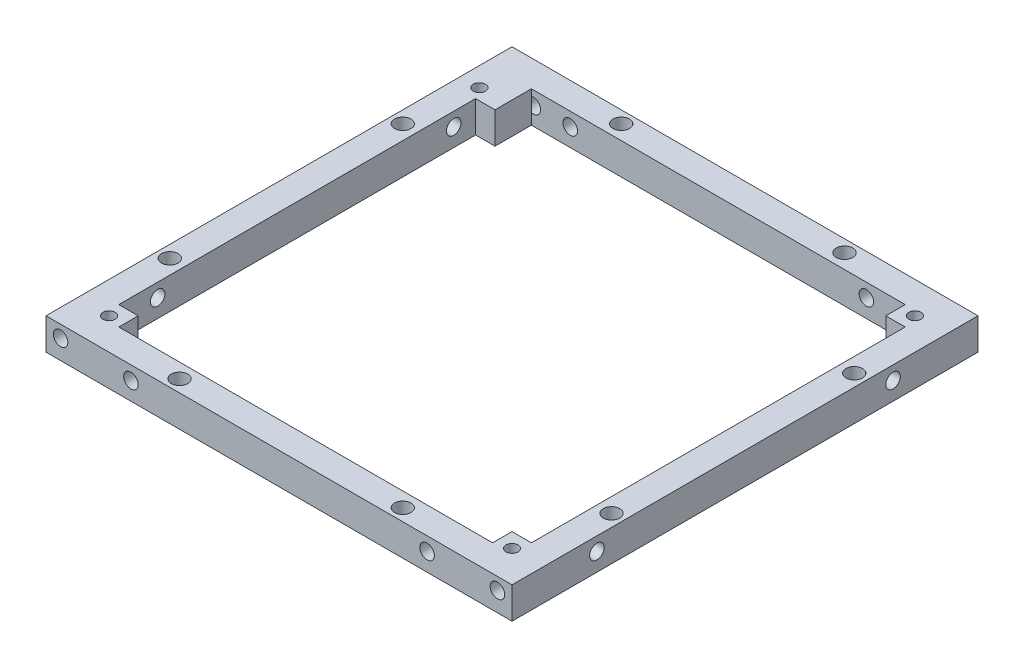
SolidWorks part; units mm, degrees
material "Aluminum"
ref_plane "Front Plane" through (0, 0, 0) normal (0, 0, 1) x (1, 0, 0)
ref_plane "Top Plane" through (0, 0, 0) normal (0, 1, 0) x (1, 0, 0)
ref_plane "Right Plane" through (0, 0, 0) normal (1, 0, 0) x (0, 0, -1)
sketch "Sketch1" plane through (0, 0, 0) normal (0, 1, 0) x (1, 0, 0)
  line L1 (48, -48) -> (-48, -48)
  line L2 (48, -48) -> (48, 48)
  line L3 (48, 48) -> (-48, 48)
  line L4 (-48, -48) -> (-48, 48)
  line L5 (48, -48) -> (-48, 48) construction
  line L6 (48, 48) -> (-48, -48) construction
  line L7 (40, -40) -> (-40, -40)
  line L8 (40, -40) -> (40, 40)
  line L9 (40, 40) -> (-40, 40)
  line L10 (-40, -40) -> (-40, 40)
  line L11 (40, -40) -> (-40, 40) construction
  line L12 (40, 40) -> (-40, -40) construction
  point P0 (0, 0)
  point P6 (0, 0)
  dimension "D1" = 96
  dimension "D2" = 96
  dimension "D3" = 8
extrude "Boss-Extrude1" add sketch "Sketch1" along normal blind 8
hole_wizard "Ø3.0 (3) Diameter Hole6" positions "Sketch8" profile "Sketch7" hole size "Ø3.0" standard "ANSI Metric"
sketch "Sketch8" plane through (0, 0, 48) normal (0, 0, 1) x (1, 0, 0)
  line L0 (48, 8) -> (48, 0) construction
  line L1 (-48, 8) -> (-48, 0) construction
  line L2 (-48, 0) -> (48, 0) construction
  point P0 (45, 4)
  point P2 (-45, 4)
  dimension "D1" = 3
  dimension "D2" = 3
  dimension "D3" = 4
  dimension "D4" = 4
sketch "Sketch7" plane through (45, 4, 48) normal (1, 0, 0) x (0, -1, 0)
  line L0 (0, 0) -> (0, 7.5)
  line L1 (0, 7.5) -> (1.5, 7.5)
  line L2 (1.5, 7.5) -> (1.5, 0)
  line L5 (1.5, 0) -> (0, 0)
  line L10 (0, 7.5) -> (-1.5, 7.5) construction
  line L11 (0, -6.35) -> (0, 107.95) construction
  dimension "Hole Dia." = 3
  dimension "Hole Depth" = 7.5
  dimension "Drill Angle" = 180
hole_wizard "Ø3.0 (3) Diameter Hole3" positions "Sketch10" profile "Sketch9" hole size "Ø3.0" standard "ANSI Metric"
sketch "Sketch10" plane through (0, 0, -48) normal (0, 0, -1) x (-1, 0, 0)
  line L0 (-48, 8) -> (-48, 0) construction
  line L1 (48, 8) -> (48, 0) construction
  line L2 (-48, 0) -> (48, 0) construction
  point P0 (-45, 4)
  point P2 (45, 4)
  dimension "D1" = 3
  dimension "D2" = 3
  dimension "D3" = 4
  dimension "D4" = 4
sketch "Sketch9" plane through (45, 4, -48) normal (1, 0, 0) x (0, 1, 0)
  line L0 (0, 0) -> (0, 7.5)
  line L1 (0, 7.5) -> (1.5, 7.5)
  line L2 (1.5, 7.5) -> (1.5, 0)
  line L5 (1.5, 0) -> (0, 0)
  line L10 (0, 7.5) -> (-1.5, 7.5) construction
  line L11 (0, -6.35) -> (0, 107.95) construction
  dimension "Hole Dia." = 3
  dimension "Hole Depth" = 7.5
  dimension "Drill Angle" = 180
sketch "Sketch27" plane through (0, 8, 0) normal (0, 1, 0) x (1, 0, 0)
  line L0 (-40, 40) -> (-40, -40) construction
  line L1 (41, -41) -> (-41, -41)
  line L2 (41, -41) -> (41, 41)
  line L3 (41, 41) -> (-41, 41)
  line L4 (-41, -41) -> (-41, 41)
  line L5 (41, -41) -> (-41, 41) construction
  line L6 (41, 41) -> (-41, -41) construction
  line L7 (40, 40) -> (-40, 40) construction
  point P0 (0, 0)
  dimension "D1" = 1
  dimension "D2" = 1
extrude "Cut-Extrude2" cut sketch "Sketch27" against normal blind 10
hole_wizard "Ø3.4 (3.4) Diameter Hole1" positions "Sketch37" profile "Sketch36" hole size "Ø3.4" standard "ANSI Metric" end condition through all
sketch "Sketch37" plane through (0, 0, 0) normal (0, -1, 0) x (-1, 0, 0)
  point P0 (-23, 45.5)
  point P2 (23, 45.5)
  point P4 (45.5, 23)
  point P6 (45.5, -25)
  point P8 (23, -45.5)
  point P10 (-23, -45.5)
  point P12 (-45.5, -25)
  point P14 (-45.5, 25)
sketch "Sketch36" plane through (23, 0, -45.5) normal (1, 0, 0) x (0, 0, -1)
  line L0 (0, 0) -> (0, 8)
  line L1 (0, 8) -> (1.7, 8)
  line L2 (1.7, 8) -> (1.7, 0)
  line L5 (1.7, 0) -> (0, 0)
  line L11 (0, -6.35) -> (0, 107.95) construction
  dimension "Thru Hole Dia." = 3.4
  dimension "Thru Hole Depth" = 8
sketch "Sketch38" plane through (0, 8, 0) normal (0, 1, 0) x (1, 0, 0)
  line L0 (48, 48) -> (-48, 48) construction
  line L1 (42.5, -42.5) -> (-42.5, -42.5)
  line L2 (42.5, -42.5) -> (42.5, 42.5)
  line L3 (42.5, 42.5) -> (-42.5, 42.5)
  line L4 (-42.5, -42.5) -> (-42.5, 42.5)
  line L5 (42.5, -42.5) -> (-42.5, 42.5) construction
  line L6 (42.5, 42.5) -> (-42.5, -42.5) construction
  line L7 (-48, 48) -> (-48, -48) construction
  point P0 (0, 0)
  dimension "D1" = 5.5
  dimension "D2" = 5.5
extrude "Cut-Extrude4" cut sketch "Sketch38" against normal blind 10
sketch "Sketch44" plane through (0, 0, 0) normal (0, -1, 0) x (1, 0, 0)
  line L0 (42.5, -42.5) -> (-42.5, -42.5) construction
  line L1 (42.5, -42.5) -> (38.5, -42.5)
  line L2 (42.5, -42.5) -> (42.5, -38.5)
  line L3 (42.5, -38.5) -> (38.5, -38.5)
  line L4 (38.5, -42.5) -> (38.5, -38.5)
  line L5 (42.5, 42.5) -> (42.5, -42.5) construction
  line L6 (0, 0) -> (0, -67.1068) construction
  line L7 (0, 0) -> (66.4168, 0) construction
  line L8 (-38.5, -42.5) -> (-38.5, -38.5)
  line L9 (-42.5, -38.5) -> (-38.5, -38.5)
  line L10 (-42.5, -42.5) -> (-42.5, -38.5)
  line L11 (-42.5, -42.5) -> (-38.5, -42.5)
  line L12 (-42.5, 42.5) -> (-38.5, 42.5)
  line L13 (-42.5, 42.5) -> (-42.5, 38.5)
  line L14 (-42.5, 38.5) -> (-38.5, 38.5)
  line L15 (-38.5, 42.5) -> (-38.5, 38.5)
  line L16 (38.5, 42.5) -> (38.5, 38.5)
  line L17 (42.5, 38.5) -> (38.5, 38.5)
  line L18 (42.5, 42.5) -> (42.5, 38.5)
  line L19 (42.5, 42.5) -> (38.5, 42.5)
  dimension "D1" = 4
  dimension "D2" = 4
extrude "Boss-Extrude2" add sketch "Sketch44" against normal blind 8
sketch "Sketch45" plane through (0, 8, 0) normal (0, 1, 0) x (1, 0, 0)
  line L1 (-42.5, 38.5) -> (-38.5, 38.5)
  line L2 (-42.5, 38.5) -> (-42.5, 35)
  line L3 (-42.5, 35) -> (-38.5, 35)
  line L4 (-38.5, 38.5) -> (-38.5, 35)
  dimension "D1" = 4
  dimension "D2" = 3.5
extrude "Boss-Extrude3" add sketch "Sketch45" against normal blind 8
hole_wizard "Tap Drill for M3x0.5 Tap1" positions "Sketch48" profile "Sketch46" hole size "M3x0.5" standard "ANSI Metric" end condition through all
sketch "Sketch48" plane through (0, 8, 0) normal (0, 1, 0) x (1, 0, 0)
  point P0 (41.5, 41.5)
  point P2 (41.5, -41.5)
  point P4 (-41.5, -41.5)
  point P6 (-44.05, 37.33)
sketch "Sketch46" plane through (41.5, 8, -41.5) normal (1, 0, 0) x (0, 0, 1)
  line L0 (0, 0) -> (0, 8)
  line L1 (0, 8) -> (1.25, 8)
  line L2 (1.25, 8) -> (1.25, 0)
  line L5 (1.25, 0) -> (0, 0)
  line L11 (0, -6.35) -> (0, 107.95) construction
  dimension "Thru Hole Dia." = 2.5
  dimension "Thru Hole Depth" = 8
sketch "Sketch49" plane through (48, 0, 0) normal (1, 0, 0) x (0, 0, -1)
  line L0 (48, 8) -> (48, 0) construction
  line L1 (-48, 8) -> (48, 8)
  line L2 (-48, 8) -> (-48, 6.5)
  line L3 (-48, 6.5) -> (48, 6.5)
  line L4 (48, 8) -> (48, 6.5)
  dimension "D1" = 1.5
extrude "Cut-Extrude5" cut sketch "Sketch49" against normal blind 146
hole_wizard "Tap Drill for M3x0.5 Tap2" positions "Sketch51" profile "Sketch50" hole size "M3x0.5" standard "ANSI Metric"
sketch "Sketch51" plane through (-48, 0, 0) normal (-1, 0, 0) x (0, 0, 1)
  point P0 (30.5, 3.7)
  point P3 (-30.5, 3.7)
sketch "Sketch50" plane through (-48, 3.7, 30.5) normal (0, 1, 0) x (0, 0, 1)
  line L0 (0, 0) -> (0, 5.5)
  line L1 (0, 5.5) -> (1.5, 5.5)
  line L2 (1.5, 5.5) -> (1.5, 0)
  line L5 (1.5, 0) -> (0, 0)
  line L11 (0, -6.35) -> (0, 107.95) construction
  dimension "Thru Hole Dia." = 3
  dimension "Thru Hole Depth" = 5.5
hole_wizard "Tap Drill for M3x0.5 Tap3" positions "Sketch53" profile "Sketch52" hole size "M3x0.5" standard "ANSI Metric"
sketch "Sketch53" plane through (0, 0, -48) normal (0, 0, -1) x (-1, 0, 0)
  point P0 (30.5, 3.7)
  point P3 (-30.5, 3.7)
sketch "Sketch52" plane through (-30.5, 3.7, -48) normal (1, 0, 0) x (0, 1, 0)
  line L0 (0, 0) -> (0, 5.5)
  line L1 (0, 5.5) -> (1.5, 5.5)
  line L2 (1.5, 5.5) -> (1.5, 0)
  line L5 (1.5, 0) -> (0, 0)
  line L11 (0, -6.35) -> (0, 107.95) construction
  dimension "Thru Hole Dia." = 3
  dimension "Thru Hole Depth" = 5.5
hole_wizard "Tap Drill for M3x0.5 Tap4" positions "Sketch55" profile "Sketch54" hole size "M3x0.5" standard "ANSI Metric" end condition up to next
sketch "Sketch55" plane through (48, 0, 0) normal (1, 0, 0) x (0, 0, -1)
  point P0 (30.5, 3.7)
  point P3 (-30.5, 3.7)
sketch "Sketch54" plane through (48, 3.7, -30.5) normal (0, 1, 0) x (0, 0, -1)
  line L0 (0, 0) -> (0, 5.5)
  line L1 (0, 5.5) -> (1.5, 5.5)
  line L2 (1.5, 5.5) -> (1.5, 0)
  line L5 (1.5, 0) -> (0, 0)
  line L11 (0, -6.35) -> (0, 107.95) construction
  dimension "Thru Hole Dia." = 3
  dimension "Thru Hole Depth" = 5.5
hole_wizard "Tap Drill for M3x0.5 Tap5" positions "Sketch57" profile "Sketch56" hole size "M3x0.5" standard "ANSI Metric" end condition up to next
sketch "Sketch57" plane through (0, 0, 48) normal (0, 0, 1) x (1, 0, 0)
  point P0 (30.5, 3.7)
  point P3 (-30.5, 3.7)
sketch "Sketch56" plane through (30.5, 3.7, 48) normal (1, 0, 0) x (0, -1, 0)
  line L0 (0, 0) -> (0, 5.5)
  line L1 (0, 5.5) -> (1.5, 5.5)
  line L2 (1.5, 5.5) -> (1.5, 0)
  line L5 (1.5, 0) -> (0, 0)
  line L11 (0, -6.35) -> (0, 107.95) construction
  dimension "Thru Hole Dia." = 3
  dimension "Thru Hole Depth" = 5.5
hole_wizard "Tap Drill for M3x0.5 Tap6" positions "Sketch59" profile "Sketch58" hole size "M3x0.5" standard "ANSI Metric"
sketch "Sketch59" plane through (0, 0, -48) normal (0, 0, -1) x (-1, 0, 0)
  line L0 (0, 0) -> (0, -19.6512) construction
  point P0 (38.1, 3.7)
  point P2 (-38.1, 3.7)
  dimension "D1" = 38.1
  dimension "D2" = 38.1
sketch "Sketch58" plane through (-38.1, 3.7, -48) normal (1, 0, 0) x (0, 1, 0)
  line L0 (0, 0) -> (0, 5.5)
  line L1 (0, 5.5) -> (1.5, 5.5)
  line L2 (1.5, 5.5) -> (1.5, 0)
  line L5 (1.5, 0) -> (0, 0)
  line L10 (0, 5.5) -> (-1.5, 5.5) construction
  line L11 (0, -6.35) -> (0, 107.95) construction
  dimension "Hole Dia." = 3
  dimension "Hole Depth" = 5.5
  dimension "Drill Angle" = 180
